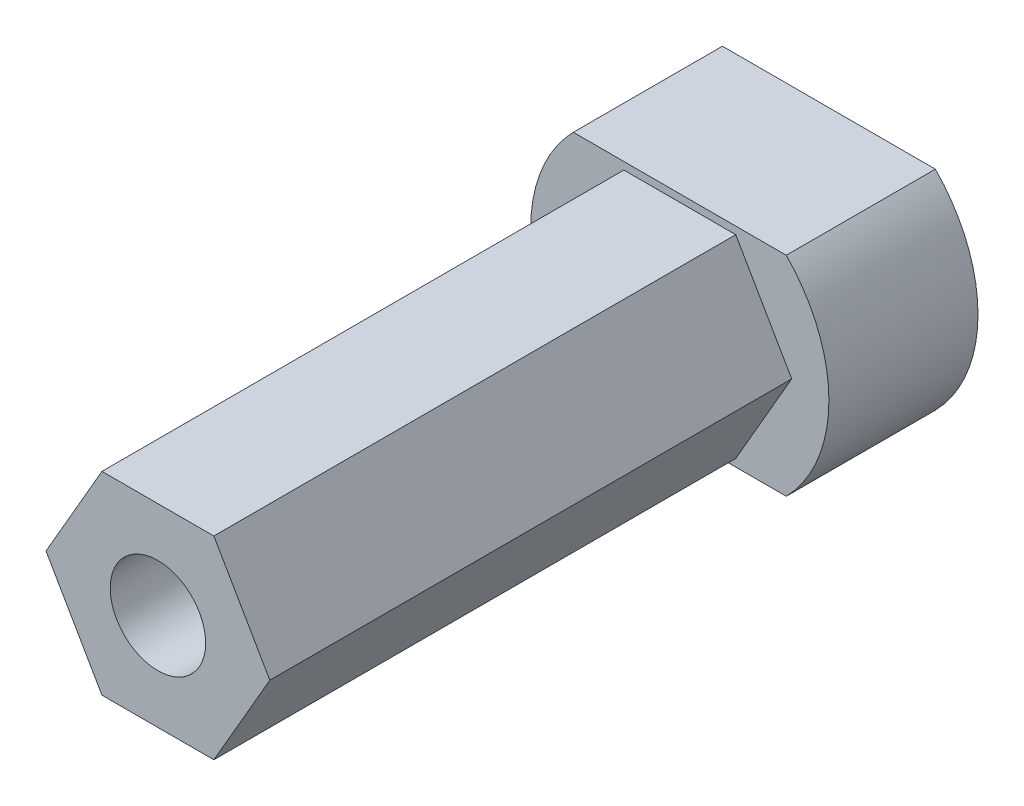
SolidWorks part; units mm, degrees
ref_plane "前视基准面" through (0, 0, 0) normal (0, 0, 1) x (1, 0, 0)
ref_plane "上视基准面" through (0, 0, 0) normal (0, 1, 0) x (1, 0, 0)
ref_plane "右视基准面" through (0, 0, 0) normal (1, 0, 0) x (0, 0, -1)
sketch "草图1" plane through (0, 0, 0) normal (0, 0, 1) x (1, 0, 0)
  line L0 (-1000, 0) -> (49000, 0) construction
  line L1 (-3.5707, 3.5) -> (3.5707, 3.5)
  line L2 (-3.5707, -3.5) -> (3.5707, -3.5)
  circle A0 centre (0, 0) radius 5
  dimension "D1" = 10
  dimension "D2" = 7
extrude "凸台-拉伸1" add sketch "草图1" along normal blind 5 contours A0 L0 L1 | L0 A0 L2
sketch "草图2" plane through (0, 0, 5) normal (0, 0, 1) x (1, 0, 0)
  line L0 (-3.5707, 3.5) -> (3.5707, 3.5) construction
  line L1 (1.8764, 3.25) -> (-1.8764, 3.25)
  line L2 (-1.8764, 3.25) -> (-3.7528, 0)
  line L3 (-3.7528, 0) -> (-1.8764, -3.25)
  line L4 (-1.8764, -3.25) -> (1.8764, -3.25)
  line L5 (1.8764, -3.25) -> (3.7528, 0)
  line L6 (3.7528, 0) -> (1.8764, 3.25)
  circle A0 centre (0, 0) radius 3.25 construction
  dimension "D1" = 6.5
extrude "凸台-拉伸2" add sketch "草图2" along normal blind 17.5
sketch "草图3" plane through (0, 0, 22.5) normal (0, 0, 1) x (1, 0, 0)
  circle A0 centre (0, 0) radius 1.6
  dimension "D1" = 3.2
extrude "切除-拉伸1" cut sketch "草图3" against normal through all
sketch "草图4" plane through (0, 0, 0) normal (0, 0, -1) x (-1, 0, 0)
  line L0 (-2.0117, 1.875) -> (2.0117, 1.875)
  line L1 (-1000, 0) -> (49000, 0) construction
  line L2 (-2.0117, -1.875) -> (2.0117, -1.875)
  circle A0 centre (0, 0) radius 2.75
  circle M5 centre (0, 0) radius 1.6
  dimension "D1" = 5.5
  dimension "D2" = 3.75
extrude "切除-拉伸2" cut sketch "草图4" against normal blind 8 contours A0 L1 L0 M5 | L1 A0 L2 M5
